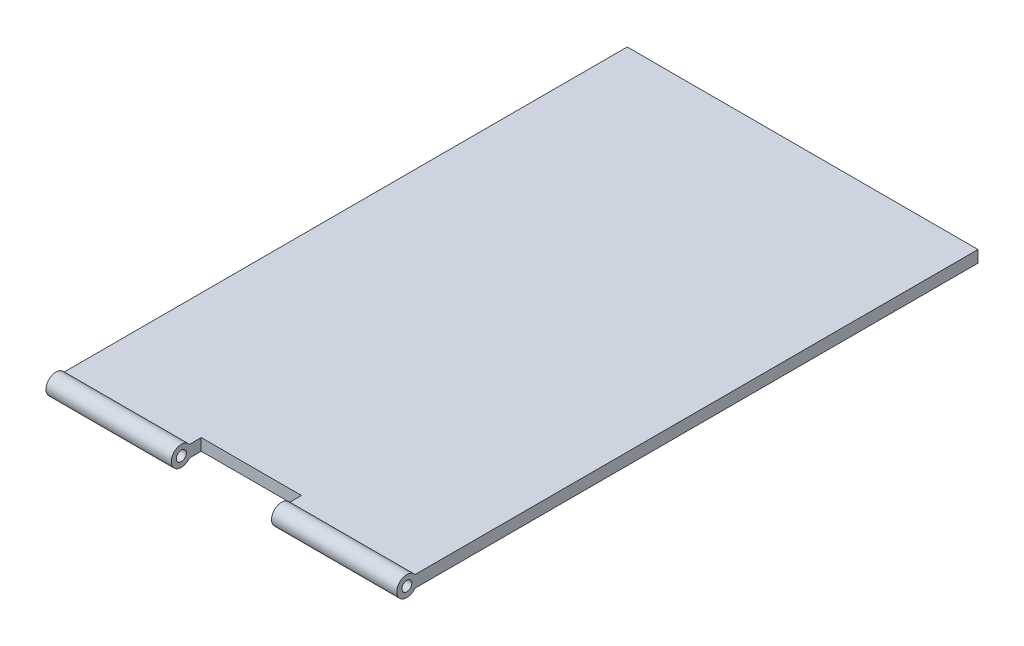
SolidWorks part; units mm, degrees
ref_plane "Front Plane" through (0, 0, 0) normal (0, 0, 1) x (1, 0, 0)
ref_plane "Top Plane" through (0, 0, 0) normal (0, 1, 0) x (1, 0, 0)
ref_plane "Right Plane" through (0, 0, 0) normal (1, 0, 0) x (0, 0, -1)
sketch "Sketch1" plane through (0, 0, 0) normal (0, 1, 0) x (1, 0, 0)
  line L1 (-44.45, 69.85) -> (44.45, 69.85)
  line L2 (-44.45, 69.85) -> (-44.45, -69.85)
  line L3 (-44.45, -69.85) -> (44.45, -69.85)
  line L4 (44.45, 69.85) -> (44.45, -69.85)
  line L5 (-44.45, 69.85) -> (44.45, -69.85) construction
  line L6 (-44.45, -69.85) -> (44.45, 69.85) construction
  point P0 (0, 0)
  dimension "D1" = 139.7
  dimension "D2" = 88.9
extrude "Boss-Extrude1" add sketch "Sketch1" along normal blind 3
sketch "Sketch3" plane through (44.45, 0, 0) normal (1, 0, 0) x (0, 0, -1)
  line L0 (-69.85, 0) -> (-69.85, 3)
  line L1 (-69.85, 3) -> (-72.85, 3)
  line L3 (-72.85, 0) -> (-69.85, 0)
  arc A0 (-72.85, 3) -> (-72.85, 0) centre (-74.8998, 1.5) ccw
  circle A1 centre (-74.8998, 1.5) radius 1.27
  dimension "D2" = 2.54
  dimension "D3" = 2.54
  dimension "D1" = 3
extrude "Boss-Extrude2" add sketch "Sketch3" against normal up to surface (88.9 mm away) up to face at (-44.45, 1.5, 0)
sketch "Sketch4" plane through (0, 0, 0) normal (0, 1, 0) x (1, 0, 0)
  line L0 (-44.45, -72.85) -> (44.45, -72.85) construction
  line L1 (-12.7, -69.85) -> (12.7, -69.85)
  line L2 (-12.7, -69.85) -> (-12.7, -87.5874)
  line L3 (-12.7, -87.5874) -> (12.7, -87.5874)
  line L4 (12.7, -69.85) -> (12.7, -87.5874)
  line L5 (-12.7, -69.85) -> (12.7, -87.5874) construction
  line L6 (-12.7, -87.5874) -> (12.7, -69.85) construction
  point P0 (0, -78.7187)
  point P7 (3.0219, -82.2277)
  point P8 (0, -72.85)
  point P9 (0, -69.85)
  dimension "D1" = 3
  dimension "D2" = 25.4
extrude "Cut-Extrude1" cut sketch "Sketch4" against normal through all both and the other way through all
